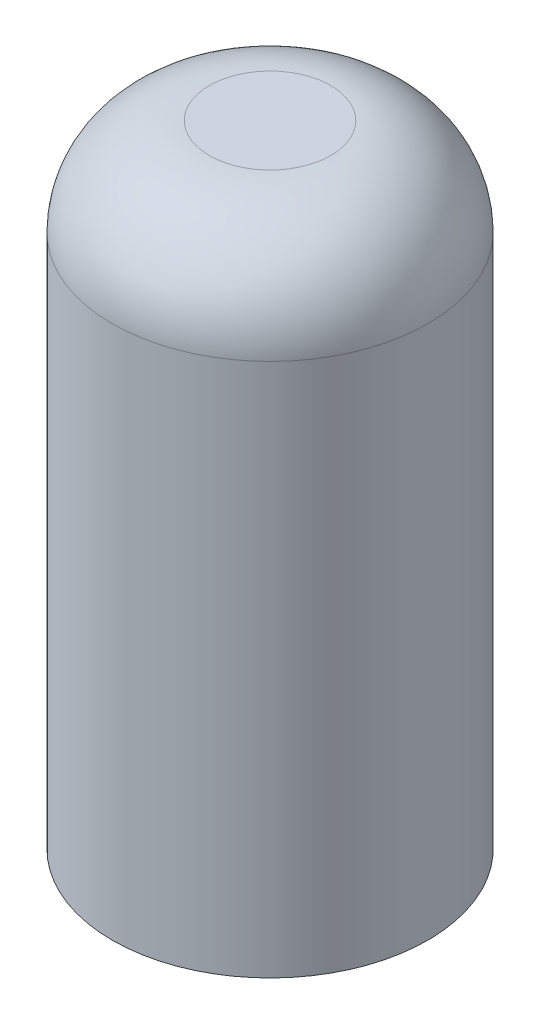
SolidWorks part; units mm, degrees
material "Glass"
ref_plane "Front Plane" through (0, 0, 0) normal (0, 0, 1) x (1, 0, 0)
ref_plane "Top Plane" through (0, 0, 0) normal (0, 1, 0) x (1, 0, 0)
ref_plane "Right Plane" through (0, 0, 0) normal (1, 0, 0) x (0, 0, -1)
sketch "Sketch1" plane through (0, 0, 0) normal (0, 1, 0) x (1, 0, 0)
  circle A0 centre (0, 0) radius 3.25
extrude "Boss-Extrude1" add sketch "Sketch1" along normal blind 13
fillet "Fillet2" radius 2 1 edges at (0, 13, 3.25)
